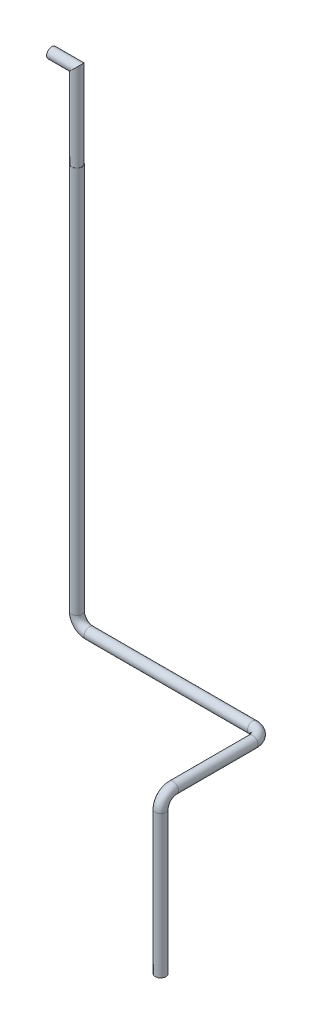
SolidWorks part; units mm, degrees
ref_plane "Alzado" through (0, 0, 0) normal (0, 0, 1) x (1, 0, 0)
ref_plane "Planta" through (0, 0, 0) normal (0, 1, 0) x (1, 0, 0)
ref_plane "Vista lateral" through (0, 0, 0) normal (1, 0, 0) x (0, 0, -1)
sketch "Croquis1" plane through (0, 0, 0) normal (0, 1, 0) x (1, 0, 0)
  circle A0 centre (0, 0) radius 12.7
  dimension "D1" = 25.4
extrude "Saliente-Extruir1" add sketch "Croquis1" along normal blind 20
sketch3d "Croquis3D1"
  line L0 (0, 20, 0) -> (0, 340, 0)
  line L1 (0, 20, 0) -> (0, 0, 0) construction
  line L2 (0, 370, -30) -> (0, 370, -220)
  line L3 (-30, 370, -250) -> (-420, 370, -250)
  line L4 (-450, 400, -250) -> (-450, 1325, -250)
  arc A0 (0, 340, 0) -> (0, 370, -30) centre (0, 340, -30) ccw
  arc A1 (0, 370, -220) -> (-30, 370, -250) centre (-30, 370, -220) ccw
  arc A2 (-420, 370, -250) -> (-450, 400, -250) centre (-420, 400, -250) ccw
  point P9 (0, 370, 0)
  point P10 (-30, 340, -30)
  point P13 (0, 370, -250)
  point P14 (-30, 400, -220)
  point P17 (-450, 370, -250)
  point P18 (-420, 400, -280)
  dimension "D5" = 30
  dimension "D6" = 30
  dimension "D7" = 30
  dimension "D1" = 350
  dimension "D2" = 250
  dimension "D3" = 450
  dimension "D4" = 955
sketch "Croquis2" plane through (0, 20, 0) normal (0, 1, 0) x (1, 0, 0)
  circle A0 centre (0, 0) radius 12.7
sweep "Barrer1" add profiles "Croquis2" path "Croquis3D1"
sketch "Croquis3" plane through (0, 1325, 0) normal (0, 1, 0) x (1, 0, 0)
  circle A0 centre (-450, 250) radius 12.25
  dimension "D1" = 24.5
extrude "Saliente-Extruir2" add sketch "Croquis3" along normal blind 150
sketch3d "Croquis3D2"
  line L0 (-450, 1475, -250) -> (-450, 1525, -250)
  line L1 (-450, 1475, -250) -> (-450, 1325, -250) construction
  line L2 (-450, 1525, -250) -> (-510, 1525, -250)
  dimension "D1" = 50
  dimension "D2" = 60
sketch "Croquis4" plane through (0, 1475, 0) normal (0, 1, 0) x (1, 0, 0)
  circle A0 centre (-450, 250) radius 12.25
sweep "Barrer2" add profiles "Croquis4" path "Croquis3D2"
